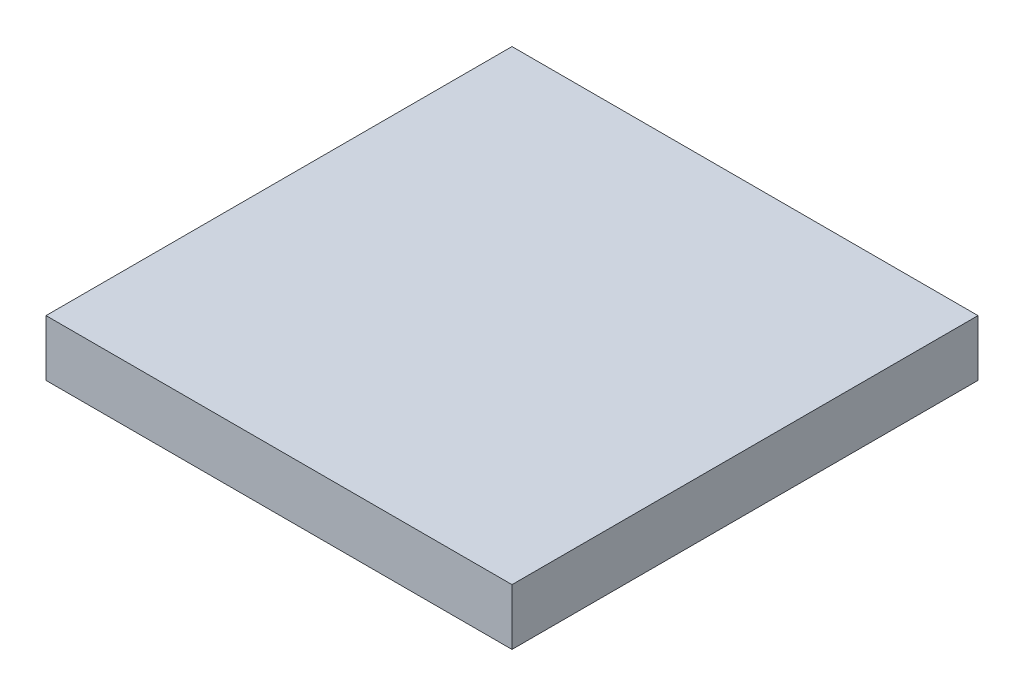
SolidWorks part; units mm, degrees
ref_plane "Front Plane" through (0, 0, 0) normal (0, 0, 1) x (1, 0, 0)
ref_plane "Top Plane" through (0, 0, 0) normal (0, 1, 0) x (1, 0, 0)
ref_plane "Right Plane" through (0, 0, 0) normal (1, 0, 0) x (0, 0, -1)
sketch "Sketch1" plane through (0, 0, 0) normal (0, 1, 0) x (1, 0, 0)
  line L1 (-4.15, -4.15) -> (4.15, -4.15)
  line L2 (-4.15, -4.15) -> (-4.15, 4.15)
  line L3 (-4.15, 4.15) -> (4.15, 4.15)
  line L4 (4.15, -4.15) -> (4.15, 4.15)
  line L5 (-4.15, -4.15) -> (4.15, 4.15) construction
  line L6 (-4.15, 4.15) -> (4.15, -4.15) construction
  point P0 (0, 0)
  dimension "D1" = 8.3
  dimension "D2" = 8.3
extrude "chip_lid" add sketch "Sketch1" along normal blind 1
equation "\"pcb_length\"= 25.0\t' length of the chip in the direction of the feadline"
equation "\"pcb_side\"= 10   \t' length of the chip in the other direction"
equation "\"pcb_width\"= 0.381\t' thickness of the PCB (381 um)"
equation "\"wall_width\"= 1 \t' minimal width from the box walls"
equation "\"route_width\"= 0.5\t' The width of the trace on the lid for not touching the signal roates."
equation "\"route_clearence\"= 0.04\t' The clearence depth of the trace on the lid for not touching the signal roates."
equation "\"route_chip_clearence\"= 1"
equation "\"port_count\"= 2"
equation "\"port_space\"= 1.5"
equation "\"port_length\"= 5.1"
equation "\"port_width\"= 5.1"
equation "\"chip_length\"= 6.3\t' length of the chip in the direction of the feadline"
equation "\"chip_side\"= 6.3\t' length of the chip in the other direction"
equation "\"pedestal_depth\"= 0.0\t' depth of the pedestal under the chip"
equation "\"chip_leg\"= 0.8 \t' size of the legs the chip lay on in case there is pedestal"
equation "\"wing_length\"= 10\t' Mounting wing size"
equation "\"wing_width\"= 1\t' mounting wing width"
equation "\"bonding_clearence\"= 0.0"
equation "\"box_height\"= \"wall_width\" + \"pedestal_depth\" + \"pcb_width\""
equation "\"box_length\"= \"pcb_length\" + 2 * \"wall_width\""
equation "\"box_side\"= \"pcb_side\" + 2 * \"wall_width\""
equation "\"D1@Sketch1\"=\"chip_length\"+2*\"wall_width\"+2*\"bonding_clearence\""
equation "\"D1@chip_lid\" = \"wall_width\""
equation "\"D2@Sketch1\"=\"chip_side\"+2*\"wall_width\"+2*\"bonding_clearence\""
equation "\"chip_width\"= 0.381\t' thickness of the chip (381 um)"
